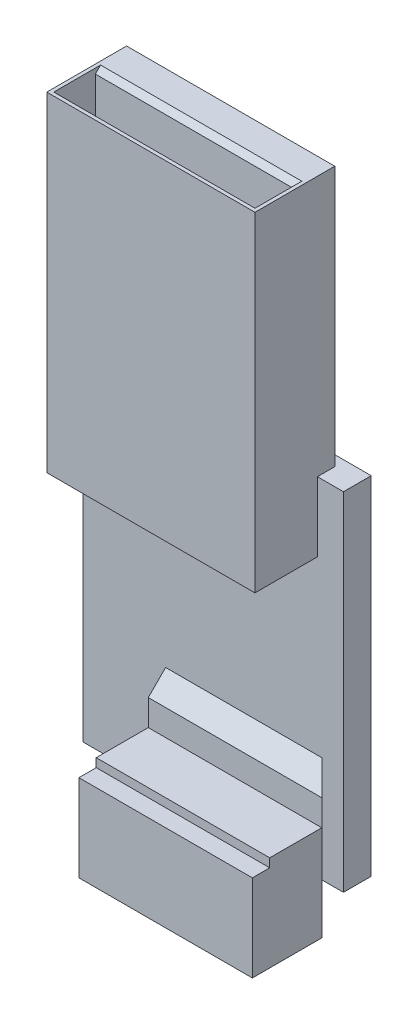
SolidWorks part; units mm, degrees
ref_plane "Front Plane" through (0, 0, 0) normal (0, 0, 1) x (1, 0, 0)
ref_plane "Top Plane" through (0, 0, 0) normal (0, 1, 0) x (1, 0, 0)
ref_plane "Right Plane" through (0, 0, 0) normal (1, 0, 0) x (0, 0, -1)
ref_plane "Plane1" through (0, -11900, 0) normal (0, -1, 0) x (1, 0, 0)
sketch "Sketch1" plane through (0, -11900, 0) normal (0, -1, 0) x (1, 0, 0)
  line L0 (6250, 1600) -> (7250, 2600)
  line L1 (7250, 2600) -> (7250, 6600)
  line L2 (7250, 6600) -> (-2750, 6600)
  line L3 (-2750, 6600) -> (-2750, 1600)
  line L4 (-2750, 1600) -> (6250, 1600)
extrude "Boss-Extrude1" add sketch "Sketch1" against normal blind 5500
sketch "Sketch2" plane through (0, -6400, 0) normal (0, 1, 0) x (-1, 0, 0)
  line L0 (2750, 2600) -> (2750, 1600)
  line L1 (2750, 1600) -> (-6250, 1600)
  line L2 (-6250, 1600) -> (-7250, 2600)
  line L3 (-7250, 2600) -> (2750, 2600)
extrude "Boss-Extrude2" add sketch "Sketch2" along normal blind 2500
sketch "Sketch3" plane through (0, 0, 1600) normal (0, 0, -1) x (-1, 0, 0)
  line L0 (-7500, -10000) -> (-7500, 10000)
  line L1 (-7500, 10000) -> (7500, 10000)
  line L2 (7500, 10000) -> (7500, -10000)
  line L3 (7500, -10000) -> (-7500, -10000)
extrude "Boss-Extrude3" add sketch "Sketch3" along normal blind 1600
sketch "Sketch4" plane through (0, 10000, 0) normal (0, 1, 0) x (-1, 0, 0)
  line L0 (6000, 1600) -> (6000, 600)
  line L1 (6000, 600) -> (-6000, 600)
  line L2 (-6000, 600) -> (-6000, 1600)
  line L3 (-6000, 1600) -> (6000, 1600)
extrude "Boss-Extrude4" add sketch "Sketch4" along normal blind 15000
sketch "Sketch5" plane through (0, 0, 1600) normal (0, 0, 1) x (1, 0, 0)
  line L0 (-6000, 6000) -> (-6000, 25000)
  line L1 (-6000, 25000) -> (6000, 25000)
  line L2 (6000, 25000) -> (6000, 6000)
  line L3 (6000, 6000) -> (-6000, 6000)
extrude "Boss-Extrude5" add sketch "Sketch5" along normal blind 3600
sketch "Sketch6" plane through (-2750, 0, 0) normal (-1, 0, 0) x (0, 0, 1)
  line L0 (5600, -6900) -> (6600, -6900)
  line L1 (6600, -6900) -> (6600, -6400)
  line L2 (6600, -6400) -> (5600, -6400)
  line L3 (5600, -6400) -> (5600, -6900)
extrude "Cut-Extrude1" cut sketch "Sketch6" against normal through all
sketch "Sketch7" plane through (0, 25000, 0) normal (0, 1, 0) x (-1, 0, 0)
  line L0 (5800, 2600) -> (5800, 5000)
  line L1 (5800, 5000) -> (-5800, 5000)
  line L2 (-5800, 5000) -> (-5800, 2600)
  line L3 (-5800, 2600) -> (5800, 2600)
extrude "Cut-Extrude2" cut sketch "Sketch7" against normal blind 9500
draft "Draft1" type of draft neutral plane draft angle 45 faces to draft 1 face at (2000, -3900, 2100) neutral plane through (0, 0, 1600) neutral plane normal (0, 0, 1) parameters "D1"=45
chamfer "Chamfer1" distance 300 angle 45 1 edges at (0, 25000, 2600)
